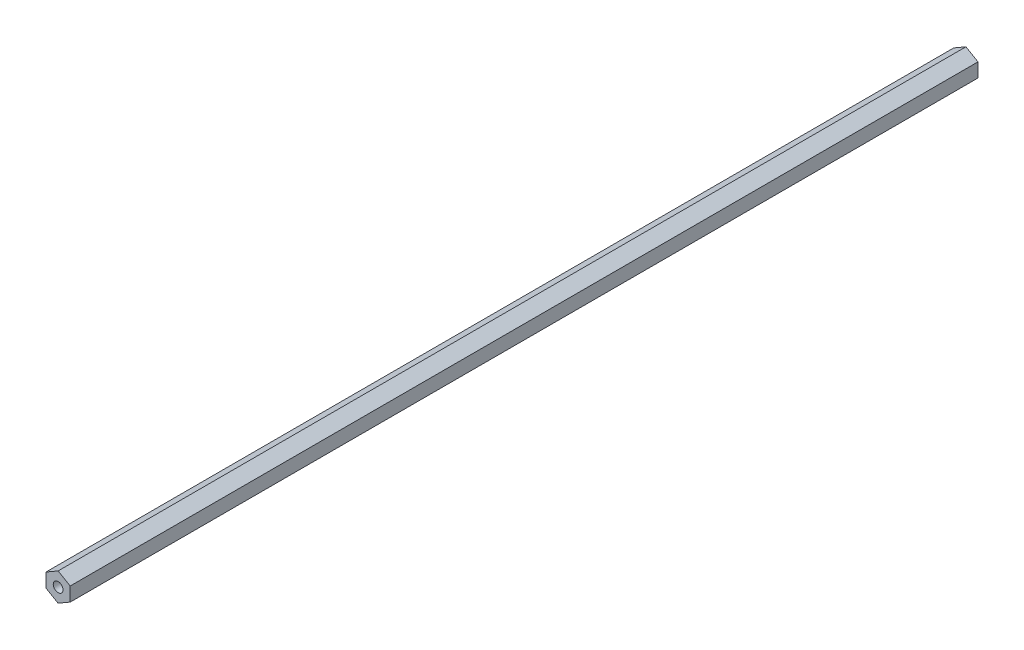
SolidWorks part; units mm, degrees
material "6061 Alloy"
ref_plane "Front Plane" through (0, 0, 0) normal (0, 0, 1) x (1, 0, 0)
ref_plane "Top Plane" through (0, 0, 0) normal (0, 1, 0) x (1, 0, 0)
ref_plane "Right Plane" through (0, 0, 0) normal (1, 0, 0) x (0, 0, -1)
sketch "Sketch1" plane through (0, 0, 0) normal (0, 0, 1) x (1, 0, 0)
  line L0 (-6.35, 0) -> (6.35, 0) construction
  line L9 (0, 7.3323) -> (-6.35, 3.6662) construction
  line L10 (-6.35, 3.6662) -> (-6.35, -3.6662) construction
  line L11 (-6.35, -3.6662) -> (0, -7.3323) construction
  line L12 (0, -7.3323) -> (6.35, -3.6662) construction
  line L13 (6.35, -3.6662) -> (6.35, 3.6662) construction
  line L14 (6.35, 3.6662) -> (0, 7.3323) construction
  circle A3 centre (0, 0) radius 6.35 construction
  point P4 (0, 0)
  dimension "Width" = 12.7
sketch "Sketch2" plane through (0, 0, 0) normal (1, 0, 0) x (0, 0, -1)
  line L0 (238.125, 7.3323) -> (-238.125, 7.3323) construction
  point P3 (-223.52, 7.3323)
  point P4 (0, 7.3323)
  point P5 (223.52, 7.3323)
  dimension "Length" = 476.25
  dimension "D1" = 14.605
  dimension "D2" = 14.605
sketch "Sketch3" plane through (0, 0, 0) normal (0, 0, 1) x (1, 0, 0)
  line L1 (0, 7.3323) -> (6.35, 3.6662)
  line L2 (6.35, 3.6662) -> (6.35, -3.6662)
  line L3 (6.35, -3.6662) -> (0, -7.3323)
  line L4 (0, -7.3323) -> (-6.35, -3.6662)
  line L5 (-6.35, -3.6662) -> (-6.35, 3.6662)
  line L6 (-6.35, 3.6662) -> (0, 7.3323)
extrude "Boss-Extrude1" add sketch "Sketch3" along normal mid plane 476.25
hole_wizard "Tap Drill for 1/4-20 Tap1" positions "Sketch4" profile "Sketch5" hole size "1/4-20" standard "ANSI Inch"
sketch "Sketch4" plane through (0, 0, 238.125) normal (0, 0, 1) x (1, 0, 0)
  point P0 (0, 0)
sketch "Sketch5" plane through (0, 0, 238.125) normal (1, 0, 0) x (0, -1, 0)
  line L0 (0, 0) -> (0, 26.9338)
  line L1 (0, 26.9338) -> (2.5527, 25.4)
  line L2 (2.5527, 25.4) -> (2.5527, 0)
  line L5 (2.5527, 0) -> (0, 0)
  line L10 (0, 26.9338) -> (-2.5527, 25.4) construction
  line L11 (0, -6.35) -> (0, 107.95) construction
  dimension "Hole Dia." = 5.1054
  dimension "Hole Depth" = 25.4
  dimension "Drill Angle" = 118
hole_wizard "Tap Drill for 1/4-20 Tap2" positions "Sketch6" profile "Sketch7" hole size "1/4-20" standard "ANSI Inch"
sketch "Sketch6" plane through (0, 0, -238.125) normal (0, 0, -1) x (-1, 0, 0)
  point P0 (0, 0)
sketch "Sketch7" plane through (0, 0, -238.125) normal (1, 0, 0) x (0, 1, 0)
  line L0 (0, 0) -> (0, 26.9338)
  line L1 (0, 26.9338) -> (2.5527, 25.4)
  line L2 (2.5527, 25.4) -> (2.5527, 0)
  line L5 (2.5527, 0) -> (0, 0)
  line L10 (0, 26.9338) -> (-2.5527, 25.4) construction
  line L11 (0, -6.35) -> (0, 107.95) construction
  dimension "Hole Dia." = 5.1054
  dimension "Hole Depth" = 25.4
  dimension "Drill Angle" = 118
equation "\"D1@Boss-Extrude1\" = \"Length@Sketch2\""
equation "\"D1@Sketch2\" = \"Width@Sketch1\" * 1.15"
equation "\"D2@Sketch2\"=\"D1@Sketch2\""
